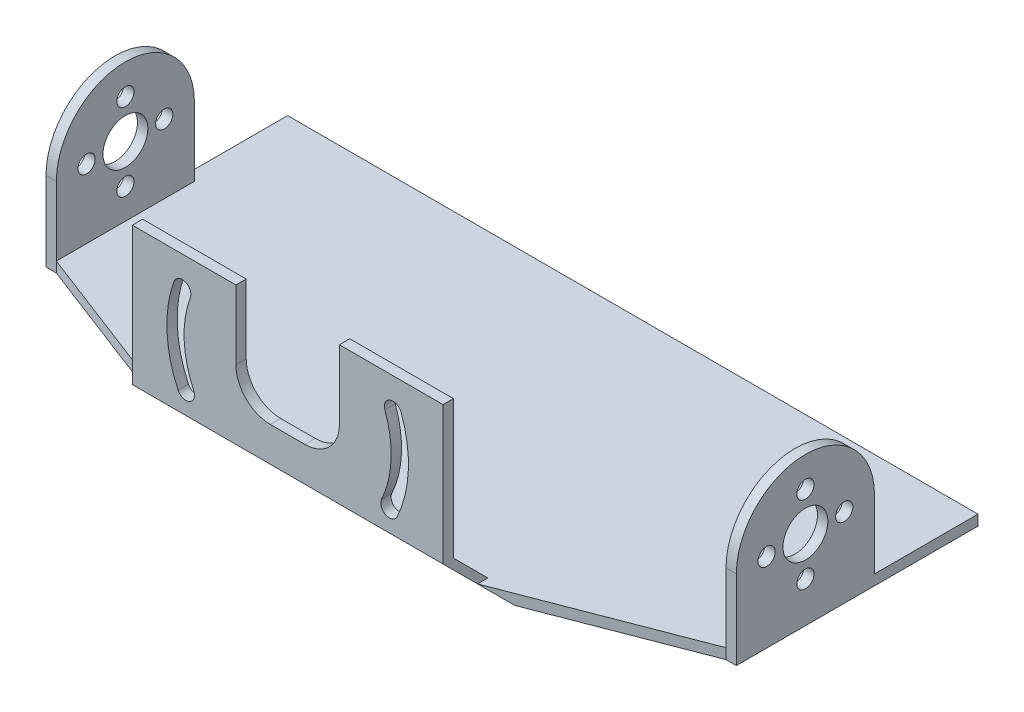
SolidWorks part; units mm, degrees
ref_plane "Front Plane" through (0, 0, 0) normal (0, 0, 1) x (1, 0, 0)
ref_plane "Top Plane" through (0, 0, 0) normal (0, 1, 0) x (1, 0, 0)
ref_plane "Right Plane" through (0, 0, 0) normal (1, 0, 0) x (0, 0, -1)
sketch "Sketch1" plane through (0, 0, 0) normal (0, 1, 0) x (1, 0, 0)
  line L1 (100, 50) -> (-100, 50)
  line L2 (100, 50) -> (100, -50)
  line L3 (100, -50) -> (-100, -50)
  line L4 (-100, 50) -> (-100, -50)
  line L5 (100, 50) -> (-100, -50) construction
  line L6 (100, -50) -> (-100, 50) construction
  point P0 (0, 0)
extrude "Boss-Extrude1" add sketch "Sketch1" along normal blind 3
sketch "Sketch2" plane through (0, 3, 0) normal (0, 1, 0) x (1, 0, 0)
  line L0 (0, -50) -> (-45, -50)
  line L1 (-100, -50) -> (100, -50) construction
  line L2 (-45, -50) -> (-45, -47)
  line L3 (-45, -47) -> (45, -47)
  line L4 (45, -47) -> (45, -50)
  line L5 (45, -50) -> (0, -50)
extrude "Boss-Extrude2" add sketch "Sketch2" along normal blind 50
sketch "Sketch3" plane through (0, 0, 50) normal (0, 0, 1) x (1, 0, 0)
  line L6 (31.7402, 18.2502) -> (29.4731, 19.3037) construction
  arc A2 (-32.8892, 44.9707) -> (-31.7402, 18.2502) centre (0, 33) ccw
  arc A3 (-28.1908, 43.2606) -> (-27.2059, 20.3573) centre (0, 33) ccw
  arc A4 (-31.7402, 18.2502) -> (-27.2059, 20.3573) centre (-29.4731, 19.3037) ccw
  arc A5 (27.2059, 20.3573) -> (31.7402, 18.2502) centre (29.4731, 19.3037) ccw
  arc A6 (32.8892, 44.9707) -> (28.1908, 43.2606) centre (30.54, 44.1157) ccw
  arc A7 (-28.1908, 43.2606) -> (-32.8892, 44.9707) centre (-30.54, 44.1157) ccw
  arc A8 (31.7402, 18.2502) -> (32.8892, 44.9707) centre (0, 33) ccw
  arc A9 (27.2059, 20.3573) -> (28.1908, 43.2606) centre (0, 33) ccw
extrude "Cut-Extrude1" cut sketch "Sketch3" against normal blind 50
sketch "Sketch4" plane through (0, 0, 50) normal (0, 0, 1) x (1, 0, 0)
  line L0 (45, 53) -> (15, 53)
  line L1 (-45, 53) -> (45, 53) construction
  line L2 (-45, 53) -> (-15, 53)
  line L3 (-15, 53) -> (-15, 33)
  line L4 (-5, 23) -> (5, 23)
  line L5 (15, 33) -> (15, 53)
  arc A0 (-15, 33) -> (-5, 23) centre (-5, 33) ccw
  arc A1 (15, 33) -> (5, 23) centre (5, 33) cw
  dimension "D1" = 10
  dimension "D2" = 10
extrude "Cut-Extrude2" cut sketch "Sketch4" against normal through all and the other way through all
sketch "Sketch5" plane through (0, 3, 0) normal (0, 1, 0) x (1, 0, 0)
  line L0 (-100, 0) -> (-100, 20)
  line L1 (-97, -20) -> (-100, -20)
  line L2 (-100, 50) -> (-100, -50) construction
  line L3 (-100, 20) -> (-97, 20)
  line L4 (-97, 20) -> (-97, -20)
  line L5 (-100, -20) -> (-100, 0)
  line L6 (100, 0) -> (100, 20)
  line L7 (100, -50) -> (100, 50) construction
  line L9 (100, 20) -> (97, 20)
  line L10 (97, 20) -> (97, -20)
  line L11 (97, -20) -> (100, -20)
  line L12 (100, -20) -> (100, 0)
extrude "Boss-Extrude4" add sketch "Sketch5" along normal blind 30
sketch "Sketch7" plane through (-100, 0, 0) normal (-1, 0, 0) x (0, 0, 1)
  line L0 (0, 33) -> (0, 23) construction
  line L1 (-20, 33) -> (20, 33) construction
  circle A0 centre (0, 23) radius 6.5
extrude "Cut-Extrude4" cut sketch "Sketch7" against normal blind 220
sketch "Sketch8" plane through (0, 33, 0) normal (0, 1, 0) x (1, 0, 0)
  line L1 (-100, 20) -> (-97, 20)
  line L2 (-100, 20) -> (-100, -20)
  line L3 (-100, -20) -> (-97, -20)
  line L4 (-97, 20) -> (-97, -20)
  line L5 (97, 20) -> (100, 20)
  line L6 (97, 20) -> (97, -20)
  line L7 (97, -20) -> (100, -20)
  line L8 (100, 20) -> (100, -20)
extrude "Boss-Extrude5" add sketch "Sketch8" along normal blind 10
sketch "Sketch9" plane through (-100, 0, 0) normal (-1, 0, 0) x (0, 0, 1)
  line L0 (0, 23) -> (-11.25, 23) construction
  line L1 (0, 23) -> (0, 34.25) construction
  line L2 (0, 23) -> (11.25, 23) construction
  line L3 (0, 23) -> (0, 11.75) construction
  circle A0 centre (0, 34.25) radius 2.5
  circle A1 centre (-11.25, 23) radius 2.5
  circle A2 centre (0, 11.75) radius 2.5
  circle A3 centre (11.25, 23) radius 2.5
extrude "Cut-Extrude5" cut sketch "Sketch9" against normal blind 247
sketch "Sketch10" plane through (0, 3, 0) normal (0, 1, 0) x (1, 0, 0)
  line L0 (-45, -50) -> (-100, -20)
  line L1 (-100, -20) -> (-100, -50)
  line L2 (-100, -50) -> (-45, -50)
extrude "Cut-Extrude6" cut sketch "Sketch10" against normal blind 29
sketch "Sketch11" plane through (0, 3, 0) normal (0, 1, 0) x (1, 0, 0)
  line L0 (45, -50) -> (100, -20)
  line L1 (100, -20) -> (100, -50)
  line L2 (100, -50) -> (45, -50)
extrude "Cut-Extrude7" cut sketch "Sketch11" against normal blind 29
sketch "Sketch12" plane through (0, 0, 50) normal (0, 0, 1) x (1, 0, 0)
  line L0 (-45, 3) -> (-45, 13)
  line L1 (-45, 53) -> (-45, 3) construction
  line L2 (-45, 13) -> (45, 13)
  line L3 (45, 53) -> (45, 3) construction
  line L4 (45, 13) -> (45, 3)
  line L5 (45, 3) -> (-45, 3)
extrude "Cut-Extrude9" cut sketch "Sketch12" against normal blind 3
sketch "Sketch13" plane through (-45, 0, 0) normal (-1, 0, 0) x (0, 0, 1)
  line L0 (47, 13) -> (37, 3)
  line L2 (47, 13) -> (50, 13)
  line L3 (47, 3) -> (37, 3)
  line L4 (47, 3) -> (50, 3)
  line L5 (50, 13) -> (50, 3)
  line L6 (50, 3) -> (20, 3) construction
extrude "Boss-Extrude6" add sketch "Sketch13" against normal blind 90
sketch "Sketch14" plane through (-45, 0, 0) normal (-1, 0, 0) x (0, 0, 1)
  line L0 (50, 13) -> (40, 3)
  line L1 (50, 3) -> (50, 53) construction
  line L2 (37, 3) -> (50, 3) construction
  line L3 (40, 3) -> (50, 3)
  line L6 (50, 3) -> (50, 13)
extrude "Cut-Extrude10" cut sketch "Sketch14" against normal blind 90
sketch "Sketch15" plane through (0, 3, 0) normal (0, 1, 0) x (1, 0, 0)
  line L0 (-100, -20) -> (-97, -20)
  line L1 (-97, -20) -> (-45, -40)
  line L2 (-45, -40) -> (45, -40)
  line L3 (45, -40) -> (97, -20)
  line L4 (97, -20) -> (100, -20)
  line L5 (100, -20) -> (45, -50)
  line L6 (45, -50) -> (-45, -50)
  line L7 (-45, -50) -> (-100, -20)
extrude "Cut-Extrude11" cut sketch "Sketch15" against normal blind 90
sketch "Sketch16" plane through (-100, 0, 0) normal (-1, 0, 0) x (0, 0, 1)
  line L0 (-20, 43) -> (20, 43)
  line L1 (20, 43) -> (20, 21.5)
  line L2 (20, 0) -> (20, 43) construction
  line L3 (-20, 43) -> (-20, 23)
  arc A0 (20, 23) -> (-20, 23) centre (0, 23) ccw
  line M8 (20, 43) -> (-20, 43)
  line M9 (-20, 43) -> (-20, 3)
extrude "Cut-Extrude12" cut sketch "Sketch16" against normal blind 217.5 contours A0 L0 M9 | A0 L1 M8
sketch "Sketch17" plane through (-45, 0, 0) normal (-1, 0, 0) x (0, 0, 1)
  line L0 (40, 3) -> (40, 0)
  line L1 (20, 0) -> (40, 0) construction
  line L2 (40, 3) -> (37, 0)
  line L3 (40, 0) -> (37, 0)
extrude "Cut-Extrude14" cut sketch "Sketch17" along normal blind 59 and the other way blind 122
